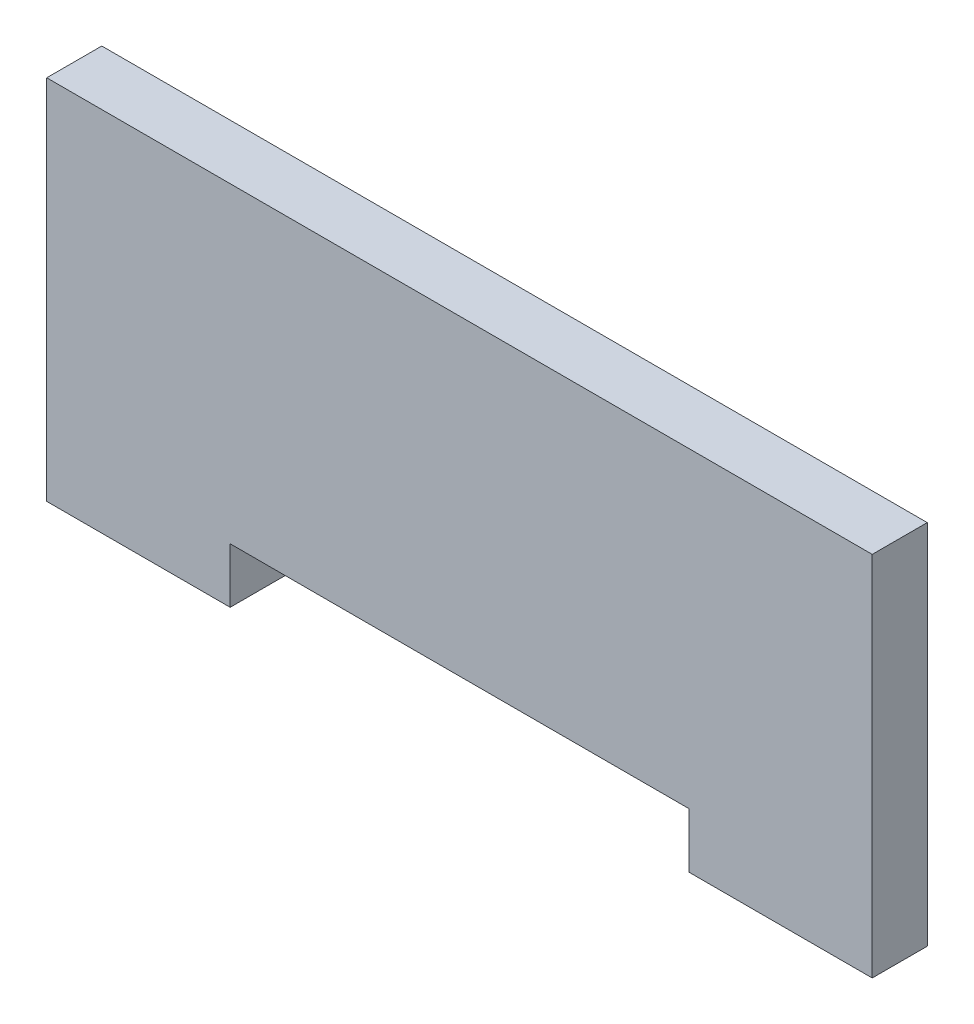
SolidWorks part; units mm, degrees
ref_plane "Front Plane" through (0, 0, 0) normal (0, 0, 1) x (1, 0, 0)
ref_plane "Top Plane" through (0, 0, 0) normal (0, 1, 0) x (1, 0, 0)
ref_plane "Right Plane" through (0, 0, 0) normal (1, 0, 0) x (0, 0, -1)
sketch "Sketch1" plane through (0, 0, 0) normal (0, 0, 1) x (1, 0, 0)
  line L1 (0, 0) -> (45, 0)
  line L2 (0, 0) -> (0, 20)
  line L3 (0, 20) -> (45, 20)
  line L4 (45, 0) -> (45, 20)
  dimension "D1" = 20
  dimension "D2" = 45
extrude "Boss-Extrude1" add sketch "Sketch1" along normal blind 3
sketch "Sketch2" plane through (0, 0, 3) normal (0, 0, 1) x (1, 0, 0)
  line L0 (0, 0) -> (45, 0) construction
  line L1 (10, 0) -> (35, 0)
  line L2 (10, 0) -> (10, 3)
  line L3 (10, 3) -> (35, 3)
  line L4 (35, 0) -> (35, 3)
  line L5 (0, 20) -> (0, 0) construction
  dimension "D1" = 3
  dimension "D2" = 25
  dimension "D3" = 10
extrude "Cut-Extrude1" cut sketch "Sketch2" against normal blind 3
